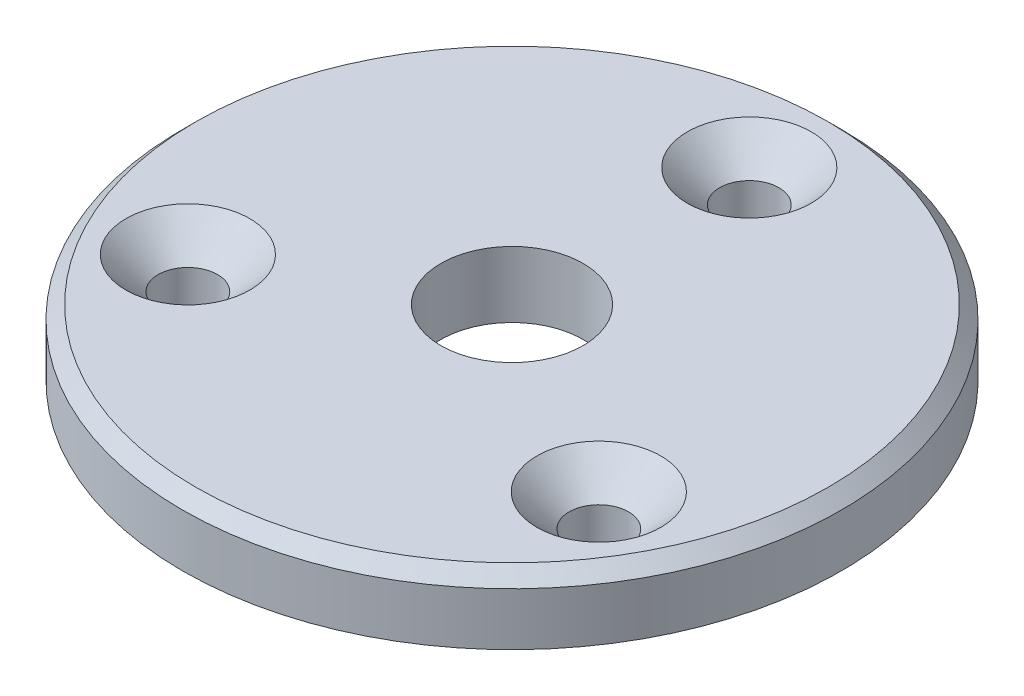
SolidWorks part; units mm, degrees
ref_plane "Front Plane" through (0, 0, 0) normal (0, 0, 1) x (1, 0, 0)
ref_plane "Top Plane" through (0, 0, 0) normal (0, 1, 0) x (1, 0, 0)
ref_plane "Right Plane" through (0, 0, 0) normal (1, 0, 0) x (0, 0, -1)
sketch "Sketch1" plane through (0, 0, 0) normal (0, 1, 0) x (1, 0, 0)
  circle A1 centre (0, 0) radius 25
  dimension "D1" = 50
extrude "Boss-Extrude1" add sketch "Sketch1" along normal blind 5
chamfer "Chamfer1" distance 1 angle 45 1 edges at (0, 5, 25)
sketch "Sketch2" plane through (0, 5, 0) normal (0, 1, 0) x (1, 0, 0)
  line L0 (0, 5.75) -> (0, 24) construction
  circle A2 centre (0, 0) radius 5.75
  circle A3 centre (0, 0) radius 24 construction
  point P4 (0, 18)
  point P7 (0, 18)
  point P8 (0, 0)
  point P11 (0, 0)
  point P12 (0, 16.8045)
  dimension "D1" = 11.5
  dimension "D2" = 6
hole_wizard "CSK for M4 Countersunk Flat Head1" positions "3DSketch1" profile "Sketch3" countersink size "M4" standard "BSI" end condition through all
sketch3d "3DSketch1"
  point P0 (0, 5, -18)
sketch "Sketch3" plane through (0, 5, -18) normal (1, 0, 0) x (0, 0, 1)
  line L0 (0, 0) -> (0, 5)
  line L1 (0, 5) -> (2.25, 5)
  line L2 (2.25, 5) -> (2.25, 2.45)
  line L3 (2.25, 2.45) -> (4.7, 0)
  line L5 (4.7, 0) -> (0, 0)
  line L6 (-2.25, 2.45) -> (-4.7, 0) construction
  line L11 (0, -6.35) -> (0, 107.95) construction
  dimension "Thru Hole Dia." = 4.5
  dimension "Thru Hole Depth" = 5
  dimension "Near C'Sink Dia." = 9.4
  dimension "Near C'Sink Angle" = 90
hole_wizard "M12x1.25 Tapped Hole1" positions "3DSketch2" profile "Sketch4" tap size "M12x1.25" standard "BSI" end condition through all
sketch3d "3DSketch2"
  point P0 (0, 0, 0)
  point P3 (0, 5, 0)
cosmetic thread "Hole Thread1" parameters "D2"=12
cosmetic thread "Hole Thread2" parameters "D2"=12
sketch "Sketch4" plane through (0, 5, 0) normal (1, 0, 0) x (0, 0, 1)
  line L0 (0, 0) -> (0, 5)
  line L1 (0, 5) -> (5.4, 5)
  line L2 (5.4, 5) -> (5.4, 0)
  line L5 (5.4, 0) -> (0, 0)
  line L11 (0, -6.35) -> (0, 107.95) construction
  dimension "Thru Tap Drill Dia." = 10.8
  dimension "Thru Tap Drill Depth" = 5
pattern_circular "CirPattern1" count 3 over 360 about axis through (0, 0, 0) along (0, 1, 0) of "CSK for M4 Countersunk Flat Head1"
